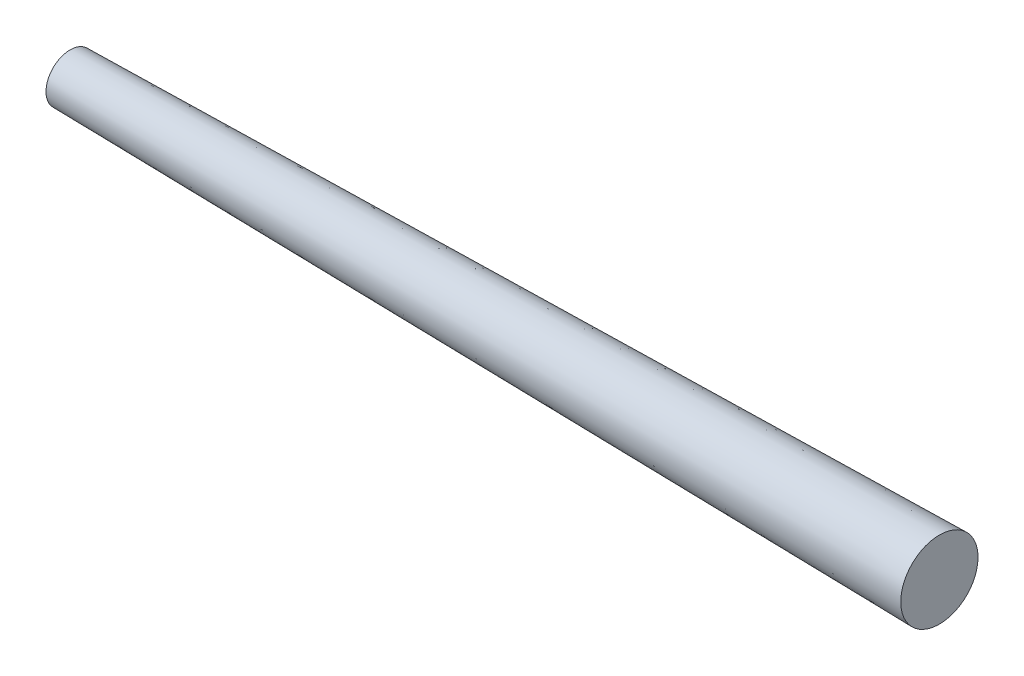
SolidWorks part; units mm, degrees
ref_plane "Ebene vorne" through (0, 0, 0) normal (0, 0, 1) x (1, 0, 0)
ref_plane "Ebene oben" through (0, 0, 0) normal (0, 1, 0) x (1, 0, 0)
ref_plane "Ebene rechts" through (0, 0, 0) normal (1, 0, 0) x (0, 0, -1)
sketch "Skizze1" plane through (0, 0, 0) normal (0, 0, 1) x (1, 0, 0)
  line L0 (-10.5382, 0) -> (-10.5382, 2.5)
  line L1 (-10.5382, 2.5) -> (79.4618, 4)
  line L2 (79.4618, 4) -> (79.4618, 0)
  line L3 (79.4618, 0) -> (-10.5382, 0)
  dimension "D1" = 2.5
  dimension "D2" = 4
  dimension "D3" = 90
revolve "Rotation1" add sketch "Skizze1" angle 360 about L3
sketch "Skizze2" plane through (79.4618, 0, 0) normal (1, 0, 0) x (0, 0, -1)
  line L0 (0, 4) -> (0, -4) construction
  line L1 (-1, 3.873) -> (-1, -3.873)
  line L2 (1, 3.873) -> (1, -3.873)
  circle A0 centre (0, 0) radius 4 construction
  dimension "D1" = 1
  dimension "D2" = 1
